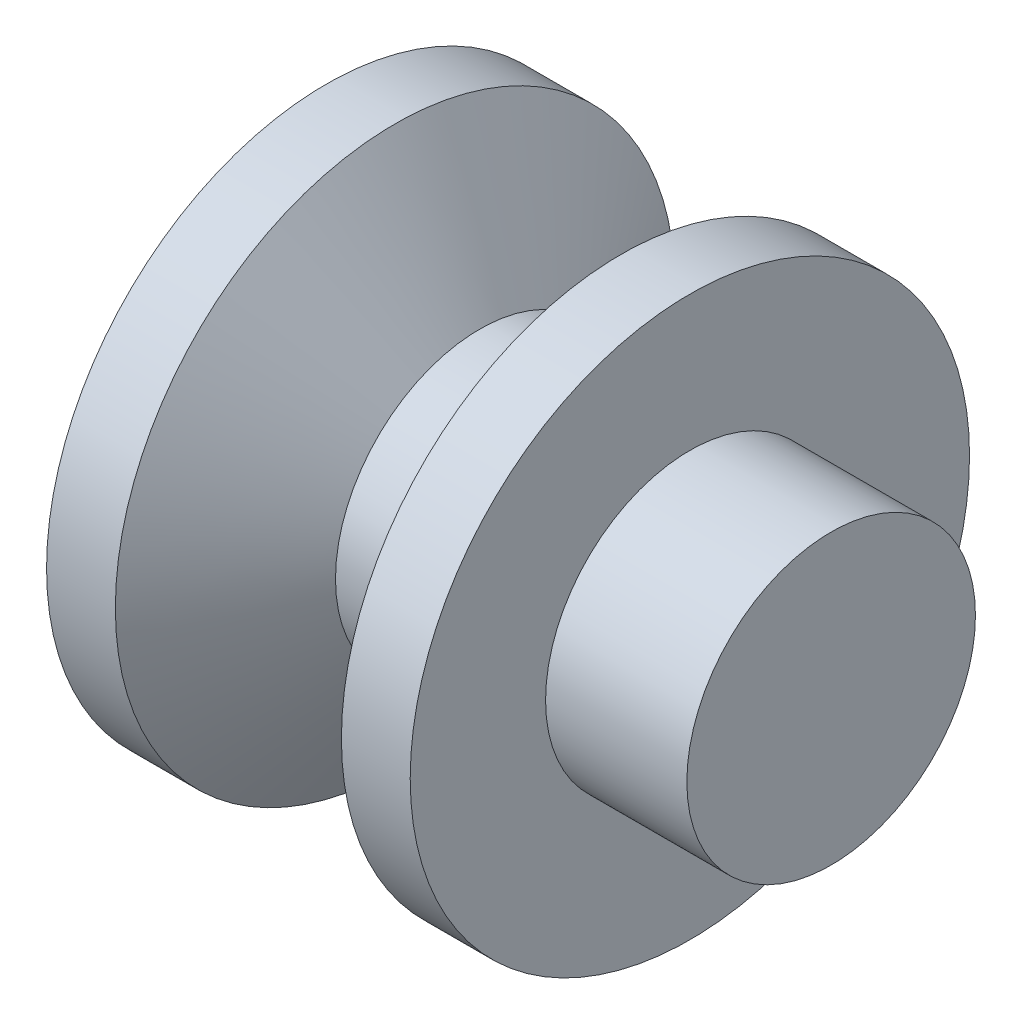
SolidWorks part; units mm, degrees
ref_plane "前基準面" through (0, 0, 0) normal (0, 0, 1) x (1, 0, 0)
ref_plane "上基準面" through (0, 0, 0) normal (0, 1, 0) x (1, 0, 0)
ref_plane "右基準面" through (0, 0, 0) normal (1, 0, 0) x (0, 0, -1)
sketch "草圖1" plane through (0, 0, 0) normal (0, 0, 1) x (1, 0, 0)
  line L0 (0, 0) -> (0, 19.795)
  line L1 (0, 19.795) -> (4.87, 19.795)
  line L2 (4.87, 19.795) -> (10.87, 10.2139)
  line L3 (10.87, 10.2139) -> (14.87, 10.2139)
  line L4 (14.87, 10.2139) -> (20.87, 19.795)
  line L5 (20.87, 19.795) -> (25.74, 19.795)
  line L6 (25.74, 19.795) -> (25.74, 10.2139)
  line L7 (25.74, 10.2139) -> (35.74, 10.2139)
  line L8 (35.74, 10.2139) -> (35.74, 0)
  line L9 (-743.1564, 0) -> (36475.4845, 0) construction
  line L10 (0, 0) -> (35.74, 0)
  dimension "D1" = 19.795
  dimension "D2" = 4.87
  dimension "D3" = 6
  dimension "D4" = 4
  dimension "D5" = 6
  dimension "D6" = 4.87
  dimension "D7" = 10
revolve "旋轉1" add sketch "草圖1" angle 360 about L9
